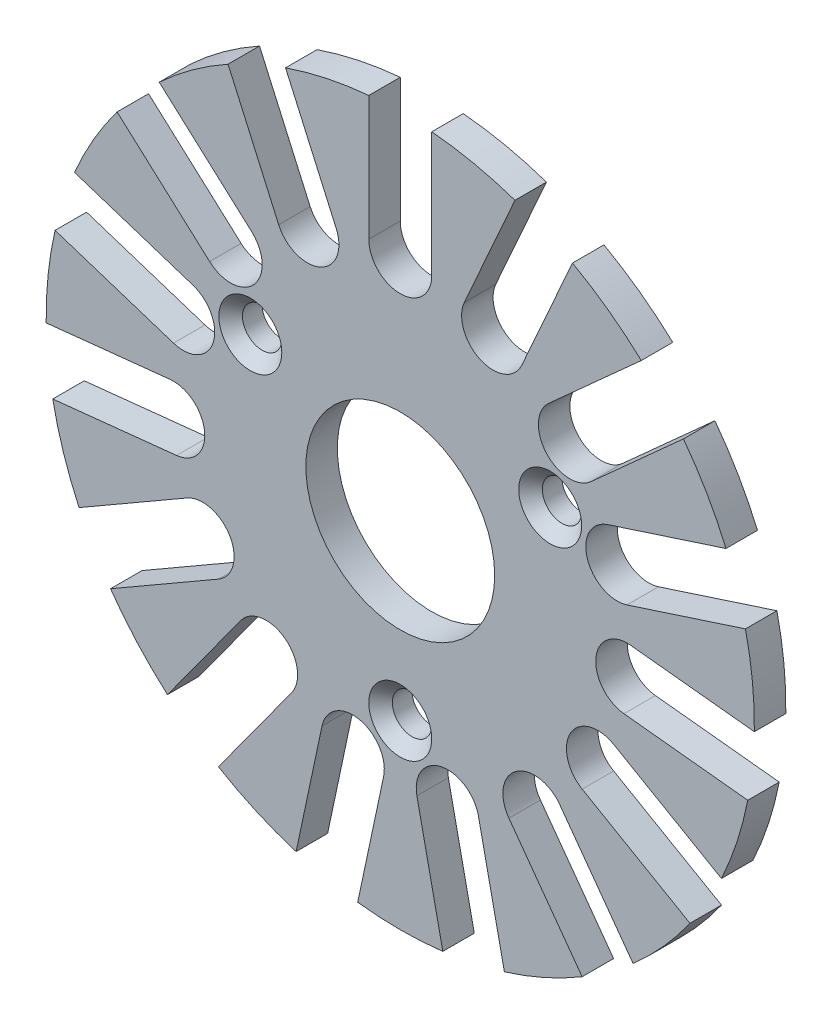
SolidWorks part; units mm, degrees
material "6061 Alloy"
ref_plane "Front Plane" through (0, 0, 0) normal (0, 0, 1) x (1, 0, 0)
ref_plane "Top Plane" through (0, 0, 0) normal (0, 1, 0) x (1, 0, 0)
ref_plane "Right Plane" through (0, 0, 0) normal (1, 0, 0) x (0, 0, -1)
ref_plane "Plane1" through (0, 0, 0) normal (0, 0, -1) x (-1, 0, 0)
sketch "Sketch1" plane through (0, 0, 0) normal (0, 0, -1) x (-1, 0, 0)
  line L0 (-15.3163, 17.1022) -> (-9.4373, 11.8087)
  line L1 (-12.1139, 8.8361) -> (-17.9928, 14.1296)
  line L2 (-20.696, 9.4475) -> (-13.1723, 7.0029)
  line L3 (-14.4084, 3.1987) -> (-21.9321, 5.6433)
  line L4 (-22.4972, 0.2665) -> (-14.6296, 1.0934)
  line L5 (-14.2115, -2.8847) -> (-22.0791, -3.7116)
  line L6 (-20.4084, -8.8534) -> (-13.5574, -4.8979)
  line L7 (-11.5574, -8.362) -> (-18.4084, -12.3175)
  line L8 (-14.7909, -16.3352) -> (-10.1409, -9.9352)
  line L9 (-6.9049, -12.2863) -> (-11.5548, -18.6864)
  line L10 (-6.6158, -20.8854) -> (-4.971, -13.1473)
  line L11 (-1.0584, -13.9789) -> (-2.7032, -21.717)
  line L12 (2.7032, -21.717) -> (1.0584, -13.9789)
  line L13 (4.971, -13.1473) -> (6.6158, -20.8854)
  line L14 (11.5548, -18.6864) -> (6.9049, -12.2863)
  line L15 (10.1409, -9.9352) -> (14.7909, -16.3352)
  line L16 (18.4084, -12.3175) -> (11.5574, -8.362)
  line L17 (13.5574, -4.8979) -> (20.4084, -8.8534)
  line L18 (22.0791, -3.7116) -> (14.2115, -2.8847)
  line L19 (14.6296, 1.0934) -> (22.4972, 0.2665)
  line L20 (21.9321, 5.6433) -> (14.4084, 3.1987)
  line L21 (13.1723, 7.0029) -> (20.696, 9.4475)
  line L22 (17.9928, 14.1296) -> (12.1139, 8.8361)
  line L23 (9.4373, 11.8087) -> (15.3163, 17.1022)
  line L24 (10.9424, 20.28) -> (7.7248, 13.053)
  line L25 (4.0706, 14.6799) -> (7.2883, 21.9069)
  line L26 (2, 23.031) -> (2, 15.12)
  line L27 (-2, 15.12) -> (-2, 23.031)
  line L28 (-7.2883, 21.9069) -> (-4.0706, 14.6799)
  line L29 (-7.7248, 13.053) -> (-10.9424, 20.28)
  circle A0 centre (9.5263, 6.12) radius 1
  circle A1 centre (-9.5263, 6.12) radius 1
  circle A2 centre (0, -10.38) radius 1
  circle A3 centre (0, 0.62) radius 6
  arc A4 (-9.4373, 11.8087) -> (-12.1139, 8.8361) centre (-10.7756, 10.3224) cw
  arc A5 (-17.9928, 14.1296) -> (-20.696, 9.4475) centre (0, 0.62) ccw
  arc A6 (-13.1723, 7.0029) -> (-14.4084, 3.1987) centre (-13.7903, 5.1008) cw
  arc A7 (-21.9321, 5.6433) -> (-22.4972, 0.2665) centre (0, 0.62) ccw
  arc A8 (-14.6296, 1.0934) -> (-14.2115, -2.8847) centre (-14.4206, -0.8956) cw
  arc A9 (-22.0791, -3.7116) -> (-20.4084, -8.8534) centre (0, 0.62) ccw
  arc A10 (-13.5574, -4.8979) -> (-11.5574, -8.362) centre (-12.5574, -6.63) cw
  arc A11 (-18.4084, -12.3175) -> (-14.7909, -16.3352) centre (0, 0.62) ccw
  arc A12 (-10.1409, -9.9352) -> (-6.9049, -12.2863) centre (-8.5229, -11.1107) cw
  arc A13 (-11.5548, -18.6864) -> (-6.6158, -20.8854) centre (0, 0.62) ccw
  arc A14 (-4.971, -13.1473) -> (-1.0584, -13.9789) centre (-3.0147, -13.5631) cw
  arc A15 (-2.7032, -21.717) -> (2.7032, -21.717) centre (0, 0.62) ccw
  arc A16 (1.0584, -13.9789) -> (4.971, -13.1473) centre (3.0147, -13.5631) cw
  arc A17 (6.6158, -20.8854) -> (11.5548, -18.6864) centre (0, 0.62) ccw
  arc A18 (6.9049, -12.2863) -> (10.1409, -9.9352) centre (8.5229, -11.1107) cw
  arc A19 (14.7909, -16.3352) -> (18.4084, -12.3175) centre (0, 0.62) ccw
  arc A20 (11.5574, -8.362) -> (13.5574, -4.8979) centre (12.5574, -6.63) cw
  arc A21 (20.4084, -8.8534) -> (22.0791, -3.7116) centre (0, 0.62) ccw
  arc A22 (14.2115, -2.8847) -> (14.6296, 1.0934) centre (14.4206, -0.8956) cw
  arc A23 (22.4972, 0.2665) -> (21.9321, 5.6433) centre (0, 0.62) ccw
  arc A24 (14.4084, 3.1987) -> (13.1723, 7.0029) centre (13.7903, 5.1008) cw
  arc A25 (20.696, 9.4475) -> (17.9928, 14.1296) centre (0, 0.62) ccw
  arc A26 (12.1139, 8.8361) -> (9.4373, 11.8087) centre (10.7756, 10.3224) cw
  arc A27 (15.3163, 17.1022) -> (10.9424, 20.28) centre (0, 0.62) ccw
  arc A28 (7.7248, 13.053) -> (4.0706, 14.6799) centre (5.8977, 13.8664) cw
  arc A29 (7.2883, 21.9069) -> (2, 23.031) centre (0, 0.62) ccw
  arc A30 (2, 15.12) -> (-2, 15.12) centre (0, 15.12) cw
  arc A31 (-2, 23.031) -> (-7.2883, 21.9069) centre (0, 0.62) ccw
  arc A32 (-4.0706, 14.6799) -> (-7.7248, 13.053) centre (-5.8977, 13.8664) cw
  arc A33 (-10.9424, 20.28) -> (-15.3163, 17.1022) centre (0, 0.62) ccw
  dimension "D1" = 2
extrude "Boss-Extrude1" add sketch "Sketch1" against normal blind 2
sketch "Sketch4" plane through (0, 0, 2) normal (0, 0, 1) x (1, 0, 0)
  point P0 (-9.5263, 6.12)
  point P1 (9.5263, 6.12)
  point P3 (0, -10.38)
hole_wizard "CSK for M3 SFHCS1" positions "3DSketch2" profile "Sketch5" countersink size "M3" standard "ANSI Metric"
sketch3d "3DSketch2"
  point P0 (-9.5263, 6.12, 2)
  point P3 (9.5263, 6.12, 2)
  point P6 (0, -10.38, 2)
sketch "Sketch5" plane through (-9.5263, 6.12, 2) normal (1, 0, 0) x (0, -1, 0)
  line L0 (0, 0) -> (0, 10.2511)
  line L1 (0, 10.2511) -> (1.25, 9.5)
  line L2 (1.25, 9.5) -> (1.25, 0.75)
  line L3 (1.25, 0.75) -> (2, 0)
  line L5 (2, 0) -> (0, 0)
  line L6 (-1.25, 0.75) -> (-2, 0) construction
  line L10 (0, 10.2511) -> (-1.25, 9.5) construction
  line L11 (0, -6.35) -> (0, 107.95) construction
  dimension "Hole Dia." = 2.5
  dimension "Hole Depth" = 9.5
  dimension "Near C'Sink Dia." = 4
  dimension "Near C'Sink Angle" = 90
  dimension "Drill Angle" = 118
